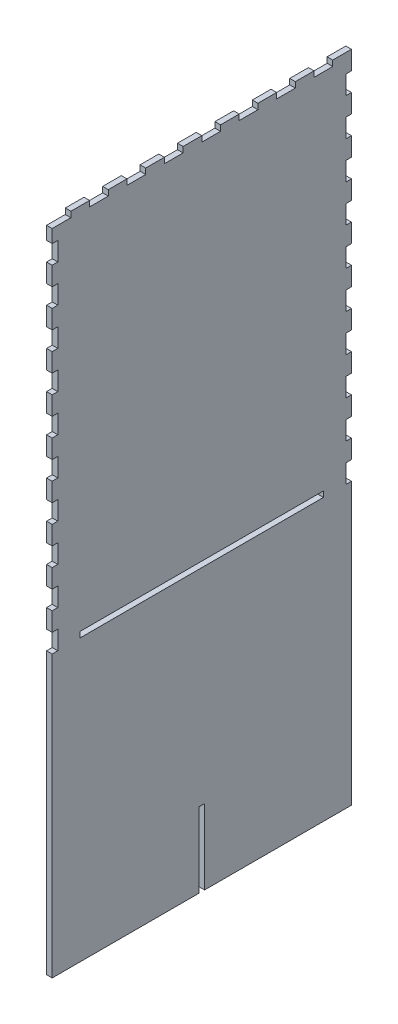
SolidWorks part; units mm, degrees
ref_plane "Alzado" through (0, 0, 0) normal (0, 0, 1) x (1, 0, 0)
ref_plane "Planta" through (0, 0, 0) normal (0, 1, 0) x (1, 0, 0)
ref_plane "Vista lateral" through (0, 0, 0) normal (1, 0, 0) x (0, 0, -1)
sketch "Croquis1" plane through (0, 0, 0) normal (1, 0, 0) x (0, 0, -1)
  line L0 (-80, -90) -> (-77, -90)
  line L1 (65, -100) -> (-65, -100)
  line L2 (-80, 97) -> (-70, 97)
  line L3 (-60, 97) -> (-50, 97)
  line L4 (0, 0) -> (0, -43.0744)
  line L5 (80, -100) -> (-80, 100) construction
  line L6 (80, 100) -> (-80, -100) construction
  line L7 (-77, -90) -> (-77, -100)
  line L8 (-80, -80) -> (-80, -90)
  line L9 (-80, -70) -> (-77, -70)
  line L10 (-77, -80) -> (-80, -80)
  line L11 (-77, -70) -> (-77, -80)
  line L12 (-80, -60) -> (-80, -70)
  line L13 (-80, -50) -> (-77, -50)
  line L14 (-77, -60) -> (-80, -60)
  line L15 (-77, -50) -> (-77, -60)
  line L16 (-80, -40) -> (-80, -50)
  line L17 (-80, -30) -> (-77, -30)
  line L18 (-77, -40) -> (-80, -40)
  line L19 (-77, -30) -> (-77, -40)
  line L20 (-80, -20) -> (-80, -30)
  line L21 (-80, -10) -> (-77, -10)
  line L22 (-77, -20) -> (-80, -20)
  line L23 (-77, -10) -> (-77, -20)
  line L24 (-80, 0) -> (-80, -10)
  line L25 (-80, 10) -> (-77, 10)
  line L26 (-77, 0) -> (-80, 0)
  line L27 (-77, 10) -> (-77, 0)
  line L28 (-80, 20) -> (-80, 10)
  line L29 (-80, 30) -> (-77, 30)
  line L30 (-77, 20) -> (-80, 20)
  line L31 (-77, 30) -> (-77, 20)
  line L32 (-80, 40) -> (-80, 30)
  line L33 (-80, 50) -> (-77, 50)
  line L34 (-77, 40) -> (-80, 40)
  line L35 (-77, 50) -> (-77, 40)
  line L36 (-80, 60) -> (-80, 50)
  line L37 (-80, 70) -> (-77, 70)
  line L38 (-77, 60) -> (-80, 60)
  line L39 (-77, 70) -> (-77, 60)
  line L40 (-77, 80) -> (-80, 80)
  line L41 (-77, 90) -> (-77, 80)
  line L42 (-80, 90) -> (-77, 90)
  line L43 (-80, 80) -> (-80, 70)
  line L44 (-80, 97) -> (-80, 90)
  line L45 (80, 100) -> (80, 90)
  line L46 (80, 80) -> (80, 70)
  line L47 (80, 90) -> (77, 90)
  line L48 (77, 90) -> (77, 80)
  line L49 (77, 80) -> (80, 80)
  line L50 (77, 70) -> (77, 60)
  line L51 (77, 60) -> (80, 60)
  line L52 (80, 70) -> (77, 70)
  line L53 (80, 60) -> (80, 50)
  line L54 (77, 50) -> (77, 40)
  line L55 (77, 40) -> (80, 40)
  line L56 (80, 50) -> (77, 50)
  line L57 (80, 40) -> (80, 30)
  line L58 (77, 30) -> (77, 20)
  line L59 (77, 20) -> (80, 20)
  line L60 (80, 30) -> (77, 30)
  line L61 (80, 20) -> (80, 10)
  line L62 (77, 10) -> (77, 0)
  line L63 (77, 0) -> (80, 0)
  line L64 (80, 10) -> (77, 10)
  line L65 (80, 0) -> (80, -10)
  line L66 (77, -10) -> (77, -20)
  line L67 (77, -20) -> (80, -20)
  line L68 (80, -10) -> (77, -10)
  line L69 (80, -20) -> (80, -30)
  line L70 (77, -30) -> (77, -40)
  line L71 (77, -40) -> (80, -40)
  line L72 (80, -30) -> (77, -30)
  line L73 (80, -40) -> (80, -50)
  line L74 (77, -50) -> (77, -60)
  line L75 (77, -60) -> (80, -60)
  line L76 (80, -50) -> (77, -50)
  line L77 (80, -60) -> (80, -70)
  line L78 (77, -70) -> (77, -80)
  line L79 (77, -80) -> (80, -80)
  line L80 (80, -70) -> (77, -70)
  line L81 (80, -80) -> (80, -90)
  line L82 (77, -90) -> (77, -100)
  line L83 (80, -90) -> (77, -90)
  line L84 (-70, 97) -> (-70, 100)
  line L85 (-70, 100) -> (-60, 100)
  line L86 (-60, 100) -> (-60, 97)
  line L87 (-50, 100) -> (-40, 100)
  line L88 (-50, 97) -> (-50, 100)
  line L89 (-40, 100) -> (-40, 97)
  line L90 (-40, 97) -> (-30, 97)
  line L91 (-30, 100) -> (-20, 100)
  line L92 (-30, 97) -> (-30, 100)
  line L93 (-20, 100) -> (-20, 97)
  line L94 (-20, 97) -> (-10, 97)
  line L95 (-10, 100) -> (0, 100)
  line L96 (-10, 97) -> (-10, 100)
  line L97 (0, 100) -> (0, 97)
  line L98 (0, 97) -> (10, 97)
  line L99 (10, 100) -> (20, 100)
  line L100 (10, 97) -> (10, 100)
  line L101 (20, 100) -> (20, 97)
  line L102 (20, 97) -> (30, 97)
  line L103 (30, 100) -> (40, 100)
  line L104 (30, 97) -> (30, 100)
  line L105 (40, 100) -> (40, 97)
  line L106 (40, 97) -> (50, 97)
  line L107 (50, 100) -> (60, 100)
  line L108 (50, 97) -> (50, 100)
  line L109 (60, 100) -> (60, 97)
  line L110 (60, 97) -> (70, 97)
  line L111 (70, 100) -> (80, 100)
  line L112 (70, 97) -> (70, 100)
  line L113 (80, 100) -> (80, 97)
  line L114 (-80, -100) -> (-80, -250)
  line L115 (-80, -250) -> (-1.5, -250)
  line L116 (80, -250) -> (80, -100)
  line L117 (-80, -100) -> (-77, -100)
  line L118 (80, -100) -> (77, -100)
  line L119 (-65, -97) -> (65, -97)
  line L120 (-65, -97) -> (-65, -100)
  line L121 (65, -97) -> (65, -100)
  line L122 (1.5, -250) -> (80, -250)
  line L123 (-0.0027, -250) -> (0.0027, -250)
  line L125 (1.5, -250) -> (1.5, -210)
  line L126 (1.5, -210) -> (-1.5, -210)
  line L127 (-1.5, -250) -> (-1.5, -210)
  line L128 (0.0027, -250) -> (-1.5, -210) construction
  line L129 (1.5, -210) -> (-0.0027, -250) construction
  point P0 (0, 0)
  dimension "D1" = 200
  dimension "D2" = 160
  dimension "D3" = 8
  dimension "D4" = 3
  dimension "D5" = 15
  dimension "D6" = 15
  dimension "D7" = 150
extrude "Saliente-Extruir1" add sketch "Croquis1" along normal blind 3
